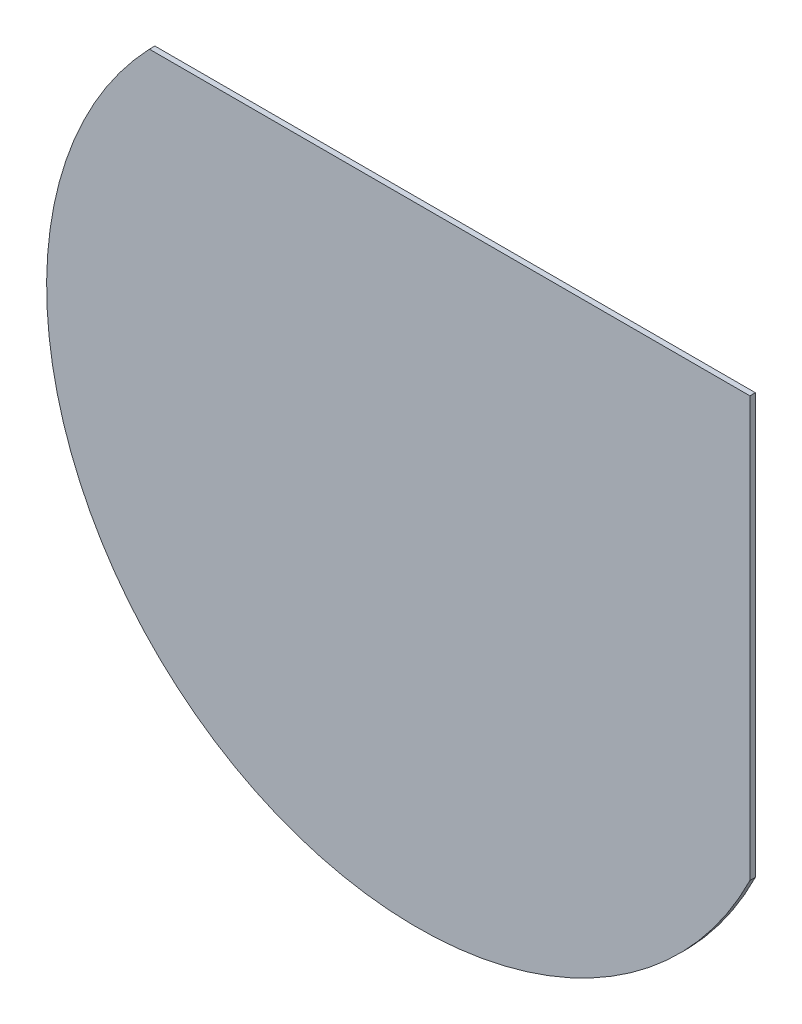
SolidWorks part; units mm, degrees
ref_plane "前视基准面" through (0, 0, 0) normal (0, 0, 1) x (1, 0, 0)
ref_plane "上视基准面" through (0, 0, 0) normal (0, 1, 0) x (1, 0, 0)
ref_plane "右视基准面" through (0, 0, 0) normal (1, 0, 0) x (0, 0, -1)
sketch "Sketch1" plane through (0, 0, 0) normal (0, 0, 1) x (1, 0, 0)
  line L0 (61.0246, 47) -> (61.0246, -30)
  line L1 (61.0246, 47) -> (-49.1426, 47)
  arc A0 (-49.1426, 47) -> (61.0246, -30) centre (0, 0) ccw
extrude "Boss-Extrude1" add sketch "Sketch1" against normal blind 1
